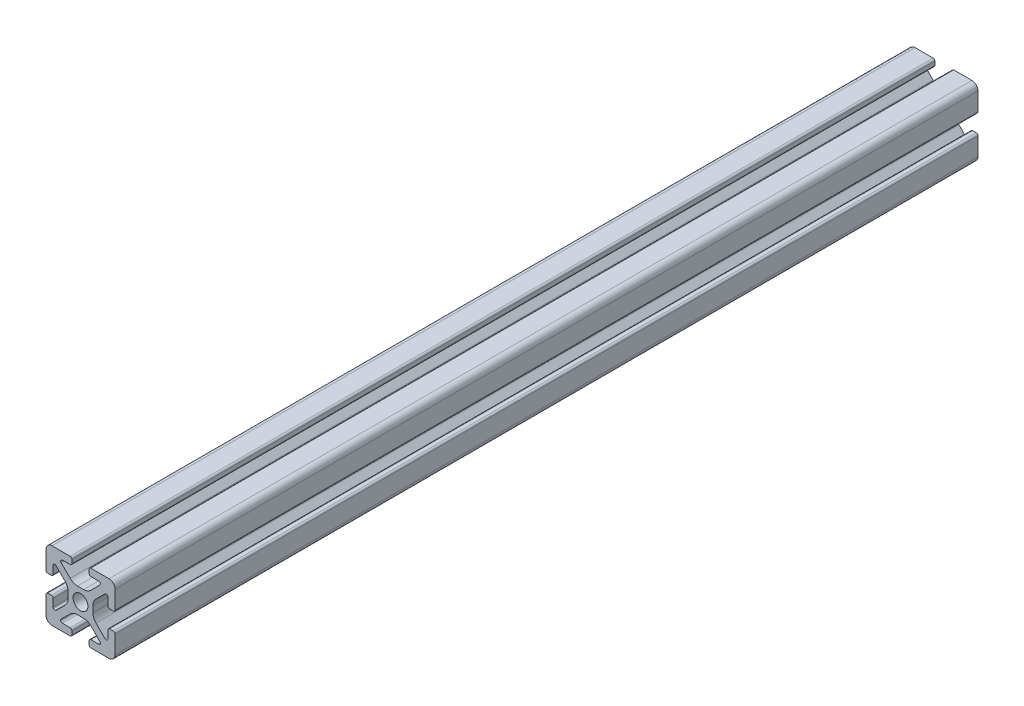
SolidWorks part; units mm, degrees
ref_plane "Front Plane" through (0, 0, 0) normal (0, 0, 1) x (1, 0, 0)
ref_plane "Top Plane" through (0, 0, 0) normal (0, 1, 0) x (1, 0, 0)
ref_plane "Right Plane" through (0, 0, 0) normal (1, 0, 0) x (0, 0, -1)
sketch "Sketch2" plane through (0, 0, 0) normal (0, 0, 1) x (1, 0, 0)
  line L0 (0, 10) -> (0, -10) construction
  line L1 (-10, 0) -> (10, 0) construction
  line L2 (2.5, -10) -> (10, -10)
  line L3 (10, -10) -> (10, -2.5)
  line L4 (2.5, -10) -> (2.5, -7.9246)
  line L5 (2.5, -7.9246) -> (6.4571, -7.9246)
  line L6 (6.4571, -7.9246) -> (2.1325, -3.6)
  line L7 (0, 0) -> (10, -10) construction
  line L8 (10, -2.5) -> (7.9246, -2.5)
  line L9 (7.9246, -2.5) -> (7.9246, -6.4571)
  line L10 (7.9246, -6.4571) -> (3.6, -2.1325)
  line L11 (5.7623, -4.2948) -> (4.2948, -5.7623) construction
  circle A0 centre (0, 0) radius 2.15
  arc A1 (5.25, -7.9246) -> (5.6036, -7.0711) centre (5.25, -7.4246) ccw construction
  point P8 (0, -3.6)
  point P16 (5.0286, -5.0286)
  dimension "Center Hole Diameter" = 4.3
  dimension "D3" = 0.5
  dimension "Rail Height" = 20
  dimension "Rail Width" = 20
  dimension "T-Slot Width" = 5
  dimension "Slot Depth" = 6.4
  dimension "Slot Inner Width" = 11.5
sketch "Sketch3" plane through (0, 0, 0) normal (1, 0, 0) x (0, 0, -1)
  line L0 (-76.2, -10) -> (76.2, -10) construction
  line L1 (-50.8, 0) -> (50.8, 0) construction
  line L2 (0, 10) -> (0, -10) construction
  line L3 (0, 10) -> (0, -10) construction
  point P6 (-50.8, 0)
  point P8 (50.8, 0)
  dimension "D1" = 25.4
  dimension "Length" = 152.4
sketch "Sketch4" plane through (0, 0, 0) normal (0, 0, 1) x (1, 0, 0)
  line L0 (3, -10) -> (8.25, -10)
  line L1 (2.5, -10) -> (10, -10) construction
  line L2 (2.5, -10) -> (2.5, -7.9246) construction
  line L3 (2.5, -7.9246) -> (6.4571, -7.9246) construction
  line L4 (2.5, -8.4246) -> (2.5, -9.5)
  line L5 (3, -7.9246) -> (5.25, -7.9246)
  line L6 (0, -3.6) -> (0.8898, -3.6)
  line L7 (6.4571, -7.9246) -> (2.1325, -3.6) construction
  line L8 (3.0112, -4.4787) -> (5.6036, -7.0711)
  line L9 (10, -10) -> (10, -2.5) construction
  line L10 (7.9246, -6.4571) -> (3.6, -2.1325) construction
  line L11 (7.9246, -2.5) -> (7.9246, -6.4571) construction
  line L12 (7.9246, -5.25) -> (7.9246, -3)
  line L13 (10, -2.5) -> (7.9246, -2.5) construction
  line L14 (8.4246, -2.5) -> (9.5, -2.5)
  line L15 (10, -3) -> (10, -8.25)
  line L16 (7.0711, -5.6036) -> (4.4787, -3.0112)
  line L17 (3.6, 0) -> (3.6, -0.8898)
  line L18 (-10, 0) -> (10, 0) construction
  line L19 (0, -3.6) -> (0, -2.15)
  line L20 (0, 10) -> (0, -10) construction
  line L21 (3.6, 0) -> (2.15, 0)
  arc A0 (2.5, -9.5) -> (3, -10) centre (3, -9.5) ccw
  arc A1 (5.25, -7.9246) -> (5.6036, -7.0711) centre (5.25, -7.4246) ccw construction
  arc A2 (2.5, -8.4246) -> (3, -7.9246) centre (3, -8.4246) cw
  arc A3 (5.25, -7.9246) -> (5.6036, -7.0711) centre (5.25, -7.4246) ccw
  arc A4 (0.8898, -3.6) -> (3.0112, -4.4787) centre (0.8898, -6.6) cw
  arc A5 (8.25, -10) -> (10, -8.25) centre (8.25, -8.25) ccw
  arc A6 (7.0711, -5.6036) -> (7.9246, -5.25) centre (7.4246, -5.25) ccw
  arc A7 (7.9246, -3) -> (8.4246, -2.5) centre (8.4246, -3) cw
  arc A8 (9.5, -2.5) -> (10, -3) centre (9.5, -3) cw
  arc A9 (4.4787, -3.0112) -> (3.6, -0.8898) centre (6.6, -0.8898) cw
  circle A10 centre (0, 0) radius 2.15 construction
  arc A11 (0, -2.15) -> (2.15, 0) centre (0, 0) ccw
  dimension "D1" = 1.75
  dimension "D2" = 3
extrude "Boss-Extrude1" add sketch "Sketch4" along normal mid plane 250
mirror "Mirror1" about plane through (0, 0, 0) normal (1, 0, 0) of bodies 134
mirror "Mirror2" about plane through (0, 0, 0) normal (0, 1, 0) of bodies 135
equation "\"D3@Sketch2\"=\"T-Slot Width@Sketch2\"*0.1"
equation "\"D1@Sketch4\"=\"D3@Sketch2\"*3.5"
equation "\"D2@Sketch4\"=\"D3@Sketch2\"*6"
equation "\"D1@Boss-Extrude1\"=110"
